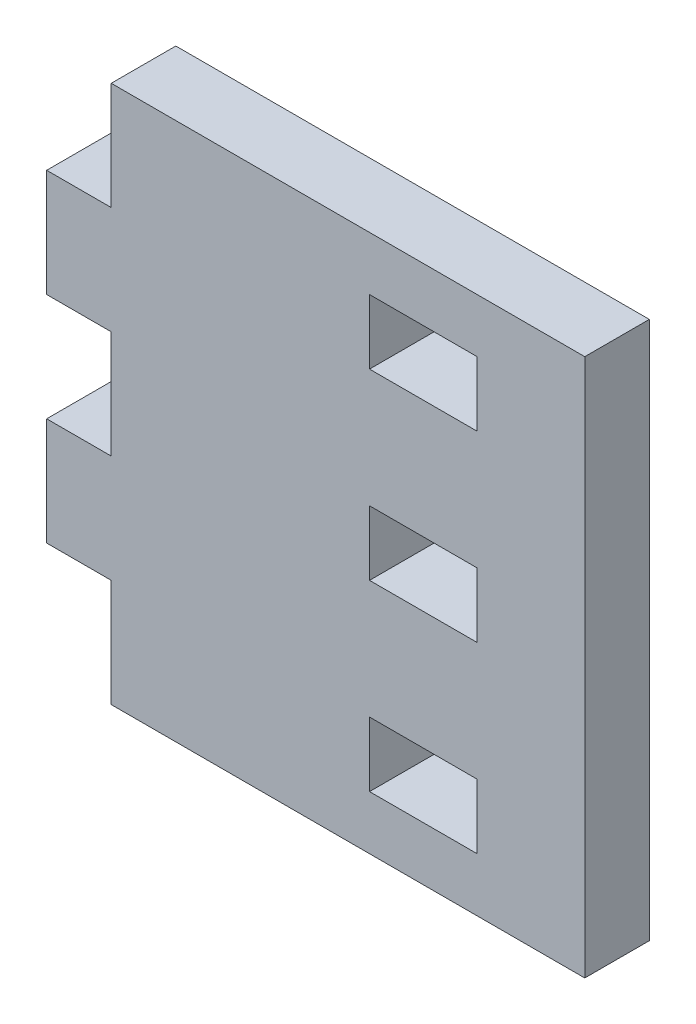
SolidWorks part; units mm, degrees
ref_plane "前基準面" through (0, 0, 0) normal (0, 0, 1) x (1, 0, 0)
ref_plane "上基準面" through (0, 0, 0) normal (0, 1, 0) x (1, 0, 0)
ref_plane "右基準面" through (0, 0, 0) normal (1, 0, 0) x (0, 0, -1)
sketch "草圖1" plane through (0, 0, 0) normal (0, 0, 1) x (1, 0, 0)
  line L0 (-33.45, 8.7375) -> (-33.45, -1.2625)
  line L1 (-33.45, 28.7375) -> (16.55, 28.7375)
  line L2 (-33.45, 28.7375) -> (-33.45, -21.2625)
  line L3 (-33.45, -21.2625) -> (16.55, -21.2625)
  line L4 (16.55, 28.7375) -> (16.55, -21.2625)
  line L5 (-33.45, 28.7375) -> (-27.45, 28.7375)
  line L6 (-33.45, 28.7375) -> (-33.45, 18.7375)
  line L7 (-33.45, 18.7375) -> (-27.45, 18.7375)
  line L8 (-27.45, 28.7375) -> (-27.45, 18.7375)
  line L9 (-33.45, 8.7375) -> (-27.45, 8.7375)
  line L10 (-27.45, 8.7375) -> (-27.45, -1.2625)
  line L11 (-33.45, -1.2625) -> (-27.45, -1.2625)
  line L12 (-33.45, -11.2625) -> (-33.45, -21.2625)
  line L13 (-33.45, -11.2625) -> (-27.45, -11.2625)
  line L14 (-27.45, -11.2625) -> (-27.45, -21.2625)
  line L15 (-33.45, -21.2625) -> (-27.45, -21.2625)
  line L20 (-3.45, 6.7375) -> (-3.45, 0.7375)
  line L21 (-3.45, 23.7375) -> (6.55, 23.7375)
  line L22 (-3.45, 23.7375) -> (-3.45, 17.7375)
  line L23 (-3.45, 17.7375) -> (6.55, 17.7375)
  line L24 (6.55, 23.7375) -> (6.55, 17.7375)
  line L25 (-3.45, 6.7375) -> (6.55, 6.7375)
  line L26 (6.55, 6.7375) -> (6.55, 0.7375)
  line L27 (-3.45, 0.7375) -> (6.55, 0.7375)
  line L28 (-3.45, -10.2625) -> (-3.45, -16.2625)
  line L29 (-3.45, -10.2625) -> (6.55, -10.2625)
  line L30 (6.55, -10.2625) -> (6.55, -16.2625)
  line L31 (-3.45, -16.2625) -> (6.55, -16.2625)
  point P23 (6.55, 20.7375)
  dimension "D1" = 6
  dimension "D2" = 10
  dimension "D3" = 50
  dimension "D5" = 50
  dimension "D6" = 6
  dimension "D7" = 10
  dimension "D9" = 5
  dimension "D10" = 5
  dimension "D11" = 10
  dimension "D12" = 10
  dimension "D4" = 3
  dimension "D8" = 3
extrude "填料-伸長1" add sketch "草圖1" along normal blind 6
